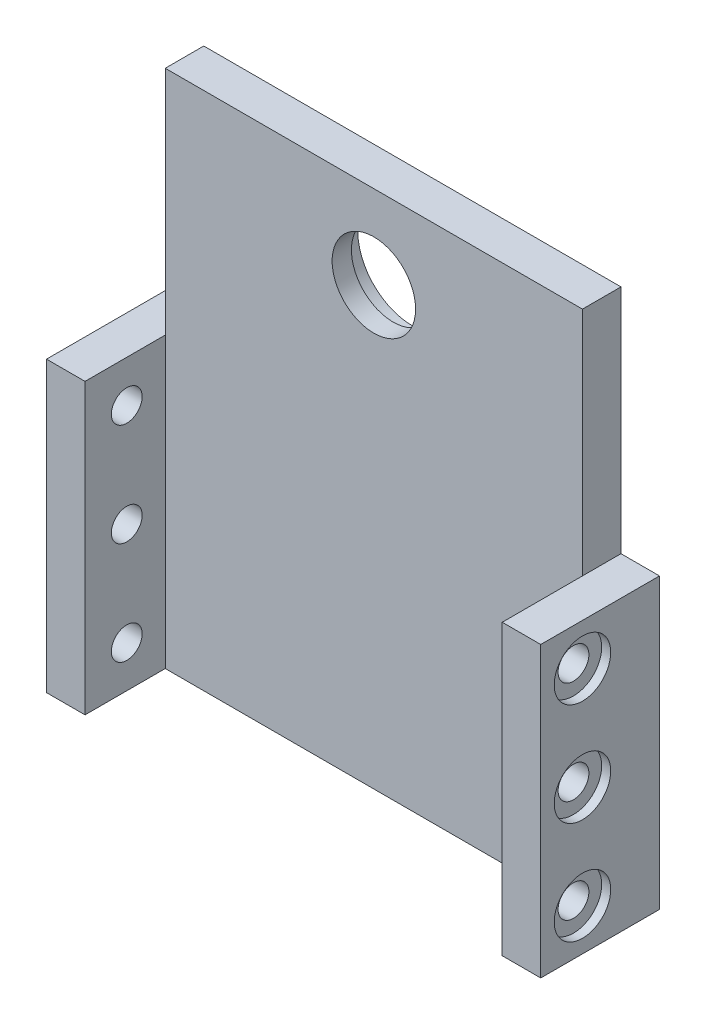
SolidWorks part; units mm, degrees
ref_plane "Plano frontal" through (0, 0, 0) normal (0, 0, 1) x (1, 0, 0)
ref_plane "Plano superior" through (0, 0, 0) normal (0, 1, 0) x (1, 0, 0)
ref_plane "Plano direito" through (0, 0, 0) normal (1, 0, 0) x (0, 0, -1)
sketch "Esboço1" plane through (0, 0, 0) normal (0, 0, 1) x (1, 0, 0)
  line L0 (16, -4.75) -> (16, -11.25) construction
  line L1 (16.25, -11.25) -> (-16.25, -11.25)
  line L2 (16.25, -11.25) -> (16.25, 29.25)
  line L3 (16.25, 29.25) -> (-16.25, 29.25)
  line L4 (-16.25, -11.25) -> (-16.25, 29.25)
  line L5 (-16, -11.25) -> (-16, -4.75) construction
  line L8 (-16.5, -11.25) -> (-10.25, -11.25) construction
  line L10 (-11, 29.25) -> (11, 29.25) construction
  dimension "D1" = 0.25
  dimension "D2" = 0.25
extrude "Ressalto-extrusão1" add sketch "Esboço1" against normal blind 3
sketch "Esboço4" plane through (-16.25, 0, 0) normal (-1, 0, 0) x (0, 0, 1)
  line L1 (-3, -11.25) -> (6.25, -11.25)
  line L2 (-3, -11.25) -> (-3, 11.25)
  line L3 (-3, 11.25) -> (6.25, 11.25)
  line L4 (6.25, -11.25) -> (6.25, 11.25)
  line L5 (6.5, -8.3463) -> (6.5, 13.8) construction
  line L6 (26.75, 11.25) -> (71.25, 11.25) construction
  dimension "D1" = 0.25
extrude "Ressalto-extrusão2" add sketch "Esboço4" along normal blind 3
mirror "Espelhar1" about plane through (0, 0, 0) normal (1, 0, 0) of "Ressalto-extrusão2"
sketch "Esboço5" plane through (0, 0, -3) normal (0, 0, -1) x (-1, 0, 0)
  circle A3 centre (0, 22.75) radius 4.25
  circle A4 centre (0, 22.75) radius 4 construction
  dimension "D1" = 0.25
extrude "Corte-extrusão1" cut sketch "Esboço5" against normal offset from surface (1.5 mm away) 1.5 up to face at (0, 9.75, 0)
sketch "Esboço6" plane through (0, 0, -3) normal (0, 0, -1) x (-1, 0, 0)
  circle A4 centre (0, 22.75) radius 3.25
  circle A5 centre (0, 22.75) radius 4 construction
  dimension "D1" = 0.75
extrude "Corte-extrusão2" cut sketch "Esboço6" against normal through all
hole_wizard "Rebaixo para parafuso com cabeça redonda de M21" positions "Esboço7" profile "Esboço8" counterbore size "M2" standard "DIN"
sketch "Esboço7" plane through (-19.25, 0, 0) normal (-1, 0, 0) x (0, 0, 1)
  circle A0 centre (3, 8) radius 1.25 construction
  point P0 (3, 8)
  point P6 (3, 0)
  point P9 (3, -8)
sketch "Esboço8" plane through (-19.25, 8, 3) normal (0, 1, 0) x (0, 0, 1)
  line L0 (0, 0) -> (0, 3)
  line L1 (0, 3) -> (1.2, 3)
  line L3 (1.2, 3) -> (1.2, 0.7)
  line L4 (1.2, 0.7) -> (2.2, 0.7)
  line L5 (2.2, 0.7) -> (2.2, 0)
  line L7 (2.2, 0) -> (0, 0)
  line L11 (0, -6.35) -> (0, 107.95) construction
  dimension "Thru Hole Dia." = 2.4
  dimension "Thru Hole Depth" = 3
  dimension "C'Bore Dia." = 4.4
  dimension "C'Bore Depth" = 0.7
mirror "Espelhar3" about plane through (0, 0, 0) normal (1, 0, 0) of "Rebaixo para parafuso com cabeça redonda de M21"
